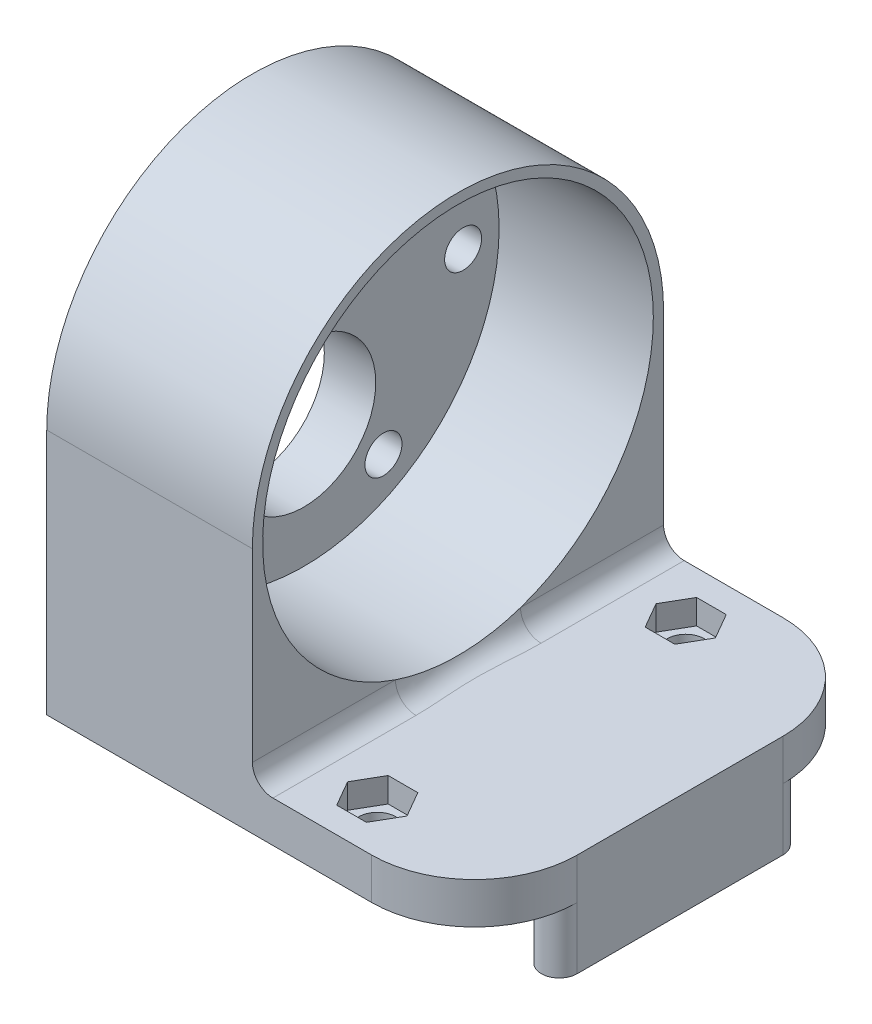
SolidWorks part; units mm, degrees
ref_plane "Plan de face" through (0, 0, 0) normal (0, 0, 1) x (1, 0, 0)
ref_plane "Plan de dessus" through (0, 0, 0) normal (0, 1, 0) x (1, 0, 0)
ref_plane "Plan de droite" through (0, 0, 0) normal (1, 0, 0) x (0, 0, -1)
sketch "Esquisse1" plane through (0, 0, 0) normal (0, 1, 0) x (1, 0, 0)
  line L1 (0, -20) -> (41.6, -20)
  line L2 (0, -20) -> (0, 20)
  line L3 (0, 20) -> (41.6, 20)
  line L4 (41.6, -20) -> (41.6, 20)
  point P4 (0, 0)
  dimension "D1" = 40
  dimension "D2" = 41.6
extrude "Boss.-Extru.1" add sketch "Esquisse1" along normal blind 4
sketch "Esquisse2" plane through (0, 0, 0) normal (-1, 0, 0) x (0, 0, 1)
  line L1 (-20, 4) -> (20, 4)
  line L2 (-20, 4) -> (-20, 24)
  line L3 (-20, 24) -> (20, 24) construction
  line L4 (20, 4) -> (20, 24)
  arc A0 (-20, 24) -> (20, 24) centre (0, 24) cw
  point P5 (0, 44)
  dimension "D1" = 40
extrude "Boss.-Extru.2" add sketch "Esquisse2" against normal blind 20
sketch "Esquisse3" plane through (20, 0, 0) normal (1, 0, 0) x (0, 0, -1)
  circle A0 centre (0, 24) radius 19
  dimension "D1" = 38
extrude "Enlèv. mat.-Extru.1" cut sketch "Esquisse3" against normal offset from surface (15 mm away) 5 up to face at (0, 17, 0)
sketch "Esquisse5" plane through (5, 0, 0) normal (1, 0, 0) x (0, 0, -1)
  line L0 (0, 24) -> (0, 17) construction
  circle A0 centre (0, 17) radius 7
  point P2 (0, 24)
  dimension "D2" = 14
  dimension "D1" = 7
extrude "Enlèv. mat.-Extru.2" cut sketch "Esquisse5" against normal up to next
sketch "Esquisse6" plane through (0, 0, 0) normal (0, -1, 0) x (1, 0, 0)
  line L0 (1.75, 10) -> (1.75, -10) construction
  line L1 (3.5, 10) -> (3.5, -10)
  line L2 (0, 10) -> (0, -10)
  line L3 (0, -20) -> (0, 20) construction
  line L4 (1.75, 0) -> (0, 0) construction
  line L5 (39.85, 10) -> (39.85, -10) construction
  line L6 (41.6, 10) -> (41.6, -10)
  line L7 (38.1, 10) -> (38.1, -10)
  arc A0 (3.5, 10) -> (0, 10) centre (1.75, 10) ccw
  arc A1 (0, -10) -> (3.5, -10) centre (1.75, -10) ccw
  arc A2 (41.6, 10) -> (38.1, 10) centre (39.85, 10) ccw
  arc A3 (38.1, -10) -> (41.6, -10) centre (39.85, -10) ccw
  point P2 (1.75, 0)
  point P15 (39.85, 0)
  dimension "D1" = 3.5
  dimension "D2" = 20
  dimension "D3" = 2
extrude "Boss.-Extru.3" add sketch "Esquisse6" along normal blind 6
hole_wizard "Dégagement M31" positions "Esquisse8" profile "Esquisse9" hole size "M3" standard "Ansi Metric" end condition through all
sketch "Esquisse8" plane through (5, 0, 0) normal (1, 0, 0) x (0, 0, -1)
  line L0 (0, 24) -> (-15.5, 24) construction
  line L2 (0, 24) -> (-7.75, 37.4234) construction
  point P0 (-15.5, 24)
  point P16 (-7.75, 37.4234)
  point P17 (7.75, 37.4234)
  point P18 (15.5, 24)
  point P19 (7.75, 10.5766)
  point P20 (-7.75, 10.5766)
  dimension "D1" = 15.5
  dimension "D3" = 60
  dimension "D2" = 6
sketch "Esquisse9" plane through (5, 24, 15.5) normal (0, 1, 0) x (0, 0, -1)
  line L0 (0, 0) -> (0, 5)
  line L1 (0, 5) -> (1.8, 5)
  line L2 (1.8, 5) -> (1.8, 0)
  line L5 (1.8, 0) -> (0, 0)
  line L11 (0, -6.35) -> (0, 107.95) construction
  dimension "Diamètre du perçage jusqu'au prochain" = 3.6
  dimension "Profondeur du perçage jusqu'au prochain" = 5
fillet "Congé1" radius 10 2 edges at (41.6, 2, -20) (41.6, 2, 20)
hole_wizard "Dégagement M32" positions "Esquisse10" profile "Esquisse11" hole size "M3" standard "Ansi Metric" end condition through all
sketch "Esquisse10" plane through (0, 4, 0) normal (0, 1, 0) x (1, 0, 0)
  line L0 (27.15, 15) -> (27.15, -15) construction
  line L2 (27.15, 0) -> (0, 0) construction
  point P0 (27.15, -15)
  point P2 (27.15, 15)
  dimension "D1" = 27.15
  dimension "D2" = 30
sketch "Esquisse11" plane through (27.15, 4, 15) normal (1, 0, 0) x (0, 0, 1)
  line L0 (0, 0) -> (0, 10)
  line L1 (0, 10) -> (1.8, 10)
  line L2 (1.8, 10) -> (1.8, 0)
  line L5 (1.8, 0) -> (0, 0)
  line L11 (0, -6.35) -> (0, 107.95) construction
  dimension "Diamètre du perçage jusqu'au prochain" = 3.6
  dimension "Profondeur du perçage jusqu'au prochain" = 10
sketch "Esquisse12" plane through (0, 4, 0) normal (0, 1, 0) x (1, 0, 0)
  line L1 (30.0368, -15) -> (28.5934, -12.5)
  line L2 (28.5934, -12.5) -> (25.7066, -12.5)
  line L3 (25.7066, -12.5) -> (24.2632, -15)
  line L4 (24.2632, -15) -> (25.7066, -17.5)
  line L5 (25.7066, -17.5) -> (28.5934, -17.5)
  line L6 (28.5934, -17.5) -> (30.0368, -15)
  line L7 (30.0368, 15) -> (28.5934, 17.5)
  line L8 (28.5934, 17.5) -> (25.7066, 17.5)
  line L9 (25.7066, 17.5) -> (24.2632, 15)
  line L10 (24.2632, 15) -> (25.7066, 12.5)
  line L11 (25.7066, 12.5) -> (28.5934, 12.5)
  line L12 (28.5934, 12.5) -> (30.0368, 15)
  circle A0 centre (27.15, -15) radius 2.5 construction
  circle A1 centre (27.15, 15) radius 2.5 construction
  dimension "D1" = 5
  dimension "D2" = 5
extrude "Enlèv. mat.-Extru.3" cut sketch "Esquisse12" against normal blind 2.4
fillet "Congé2" radius 2 1 edges at (20, 4, 0)
